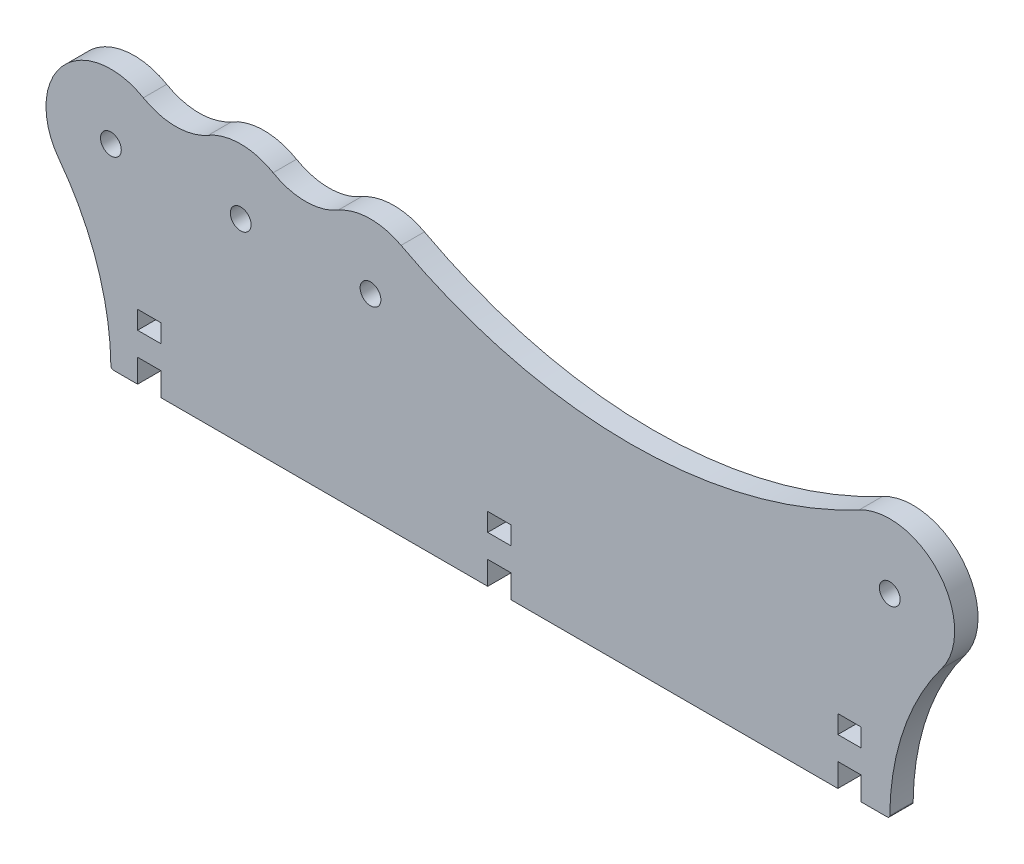
SolidWorks part; units mm, degrees
ref_plane "Front Plane" through (0, 0, 0) normal (0, 0, 1) x (1, 0, 0)
ref_plane "Top Plane" through (0, 0, 0) normal (0, 1, 0) x (1, 0, 0)
ref_plane "Right Plane" through (0, 0, 0) normal (1, 0, 0) x (0, 0, -1)
sketch "Sketch1" plane through (0, 0, 0) normal (0, 0, 1) x (1, 0, 0)
  line L0 (-125, 0) -> (125, 0) construction
  circle A0 centre (-125, 0) radius 4
  circle A1 centre (125, 0) radius 4
  circle A2 centre (-125, 0) radius 8
  circle A3 centre (125, 0) radius 8
  dimension "D1" = 8
  dimension "D3" = 16
  dimension "D2" = 250
extrude "Boss-Extrude1" add sketch "Sketch1" along normal blind 9
sketch "Sketch2" plane through (0, 0, 0) normal (0, 0, 1) x (1, 0, 0)
  line L0 (-125, -25) -> (125, -25) construction
  line L1 (0, -25) -> (0, -75) construction
  line L2 (-125, -75) -> (125, -75)
  line L3 (-125, -75) -> (-125, -25) construction
  line L4 (-175, 0) -> (-125, 0) construction
  line L5 (-175, 0) -> (-175, -75) construction
  line L6 (-125, 0) -> (125, 0) construction
  line L7 (-175, -75) -> (-125, -75)
  line L8 (-275, -75) -> (-175, -75) construction
  line L9 (225, -75) -> (125, -75) construction
  circle A0 centre (-125, 0) radius 25
  circle A1 centre (-125, 0) radius 4
  circle A2 centre (-125, 0) radius 4 construction
  circle A3 centre (125, 0) radius 4
  circle A4 centre (125, 0) radius 25
  circle A5 centre (125, 0) radius 4 construction
  circle A9 centre (-75, 0) radius 4
  circle A10 centre (-175, 0) radius 4
  circle A13 centre (-175, 0) radius 25
  circle A14 centre (-75, 0) radius 25
  circle A15 centre (-275, -75) radius 100
  circle A16 centre (225, -75) radius 100
  circle A17 centre (25, 187.5) radius 187.5
  circle A18 centre (-150, 43.3013) radius 25
  circle A19 centre (-100, 43.3013) radius 25
  dimension "D2" = 50
  dimension "D3" = 50
  dimension "D1" = 50
  dimension "D4" = 50
extrude "Boss-Extrude3" add sketch "Sketch2" along normal blind 9 contours A17 A14 A0 A13 A15 L7 L2 A16 A4 | A4 A3 | A14 A9 | A19 A0 A14 | A0 A1 | A18 A13 A0 | A13 A10
fillet "Fillet1" radius 1 2 edges at (125, -75, 4.5) (-175, -75, 4.5)
sketch "Sketch3" plane through (0, 0, 0) normal (0, 0, 1) x (1, 0, 0)
  line L0 (-174.005, -75) -> (124.005, -75) construction
  line L1 (-164.7085, -75) -> (-155.7085, -75)
  line L2 (-164.7085, -75) -> (-164.7085, -66)
  line L3 (-164.7085, -66) -> (-155.7085, -66)
  line L4 (-155.7085, -75) -> (-155.7085, -66)
  line L5 (-155.7085, -66) -> (-29.8518, -66) construction
  line L6 (-29.8518, -75) -> (-20.8518, -75)
  line L7 (-29.8518, -75) -> (-29.8518, -66)
  line L8 (-29.8518, -66) -> (-20.8518, -66)
  line L9 (-20.8518, -75) -> (-20.8518, -66)
  line L10 (105.005, -75) -> (114.005, -75)
  line L11 (105.005, -75) -> (105.005, -66)
  line L12 (105.005, -66) -> (114.005, -66)
  line L13 (114.005, -75) -> (114.005, -66)
  line L14 (-164.7085, -57) -> (-155.7085, -57)
  line L15 (-164.7085, -57) -> (-164.7085, -50)
  line L16 (-164.7085, -50) -> (-155.7085, -50)
  line L17 (-155.7085, -57) -> (-155.7085, -50)
  line L18 (-29.8518, -57) -> (-20.8518, -57)
  line L19 (-29.8518, -57) -> (-29.8518, -50)
  line L20 (-29.8518, -50) -> (-20.8518, -50)
  line L21 (-20.8518, -57) -> (-20.8518, -50)
  line L22 (105.005, -57) -> (114.005, -57)
  line L23 (105.005, -57) -> (105.005, -50)
  line L24 (105.005, -50) -> (114.005, -50)
  line L25 (114.005, -57) -> (114.005, -50)
  line L26 (-20.8518, -66) -> (105.005, -66) construction
  line L27 (105.005, -57) -> (105.005, -66) construction
  line L28 (105.005, -57) -> (-20.8518, -57) construction
  line L29 (-29.8518, -57) -> (-29.8518, -66) construction
  line L30 (-20.8518, -66) -> (-20.8518, -57) construction
  line L31 (-29.8518, -57) -> (-155.7085, -57) construction
  line L32 (-164.7085, -57) -> (-164.7085, -66) construction
  line L33 (114.005, -66) -> (114.005, -57) construction
  line L34 (-155.7085, -57) -> (-155.7085, -66) construction
  line L35 (-155.7085, -50) -> (-29.8518, -50) construction
  line L36 (-20.8518, -50) -> (105.005, -50) construction
  arc A0 (-175.0049, -74.0099) -> (-174.005, -75) centre (-174.005, -74) ccw construction
  arc A1 (124.005, -75) -> (125.0049, -74.0099) centre (124.005, -74) ccw construction
  point P29 (-174.7085, -74.7106)
  dimension "D1" = 9
  dimension "D2" = 9
  dimension "D3" = 25
  dimension "D4" = 9
  dimension "D5" = 10
  dimension "D6" = 10
extrude "Cut-Extrude1" cut sketch "Sketch3" along normal through all
